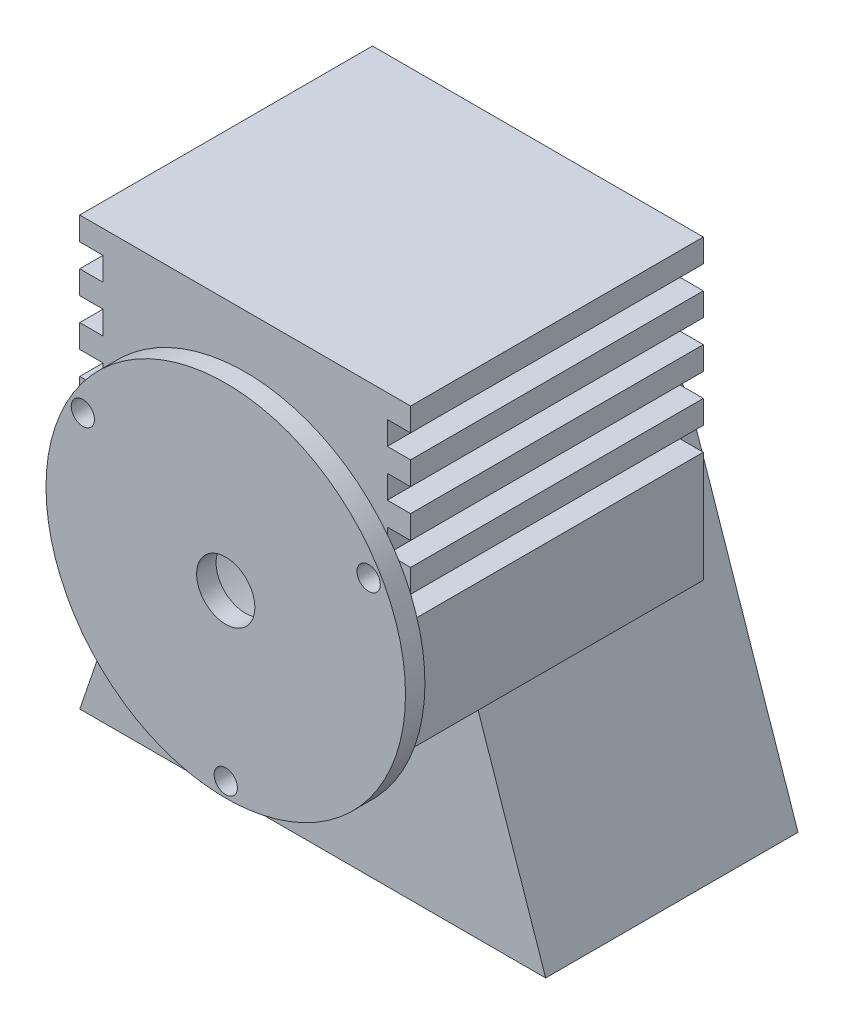
SolidWorks part; units mm, degrees
ref_plane "Front Plane" through (0, 0, 0) normal (0, 0, 1) x (1, 0, 0)
ref_plane "Top Plane" through (0, 0, 0) normal (0, 1, 0) x (1, 0, 0)
ref_plane "Right Plane" through (0, 0, 0) normal (1, 0, 0) x (0, 0, -1)
sketch "Sketch1" plane through (0, 0, 0) normal (0, 0, 1) x (1, 0, 0)
  line L0 (-150, -169) -> (150, -169)
  line L1 (-150, -169) -> (-82.8271, 28.212)
  line L3 (82.8271, 28.212) -> (150, -169)
  arc A0 (82.8271, 28.212) -> (-82.8271, 28.212) centre (0, 0) ccw
  point P5 (0, -169)
  dimension "D1" = 175
  dimension "D2" = 300
  dimension "D3" = 169
extrude "Boss-Extrude1" add sketch "Sketch1" along normal blind 162.5
sketch "Sketch2" plane through (0, 0, 162.5) normal (0, 0, 1) x (1, 0, 0)
  line L0 (-106.5324, 150) -> (106.5324, 150)
  line L1 (-106.5324, 150) -> (-106.5324, 135)
  line L2 (-106.5324, 135) -> (-91.5324, 135)
  line L3 (-91.5324, 135) -> (-91.5324, 120)
  line L4 (-91.5324, 120) -> (-106.5324, 120)
  line L5 (-106.5324, 120) -> (-106.5324, 105)
  line L6 (-106.5324, 105) -> (-91.5324, 105)
  line L7 (-91.5324, 105) -> (-91.5324, 90)
  line L8 (-91.5324, 90) -> (-106.5324, 90)
  line L9 (-106.5324, 90) -> (-106.5324, 75)
  line L10 (-106.5324, 75) -> (-91.5324, 75)
  line L11 (-91.5324, 75) -> (-91.5324, 60)
  line L12 (-91.5324, 60) -> (-106.5324, 60)
  line L13 (-106.5324, 60) -> (-106.5324, 45)
  line L14 (-106.5324, 45) -> (-91.5324, 45)
  line L15 (-91.5324, 45) -> (-91.5324, 30)
  line L16 (-91.5324, 30) -> (-106.5324, 30)
  line L17 (-106.5324, 30) -> (-106.5324, -41.3841)
  line L18 (-106.5324, -41.3841) -> (-82.8271, 28.212)
  line L19 (0, 0) -> (0, 150) construction
  line L20 (91.5324, 30) -> (106.5324, 30)
  line L21 (91.5324, 45) -> (91.5324, 30)
  line L22 (106.5324, 45) -> (91.5324, 45)
  line L23 (106.5324, 60) -> (106.5324, 45)
  line L24 (91.5324, 60) -> (106.5324, 60)
  line L25 (91.5324, 75) -> (91.5324, 60)
  line L26 (106.5324, 75) -> (91.5324, 75)
  line L27 (106.5324, 90) -> (106.5324, 75)
  line L28 (91.5324, 90) -> (106.5324, 90)
  line L29 (91.5324, 105) -> (91.5324, 90)
  line L30 (106.5324, 105) -> (91.5324, 105)
  line L31 (106.5324, 120) -> (106.5324, 105)
  line L32 (91.5324, 120) -> (106.5324, 120)
  line L33 (91.5324, 135) -> (91.5324, 120)
  line L34 (106.5324, 135) -> (91.5324, 135)
  line L35 (106.5324, 150) -> (106.5324, 135)
  line L36 (106.5324, 30) -> (106.5324, -41.3841)
  line L37 (106.5324, -41.3841) -> (82.8271, 28.212)
  arc A0 (82.8271, 28.212) -> (-82.8271, 28.212) centre (0, 0) ccw
  point P2 (0, 150)
  dimension "D1" = 150
  dimension "D2" = 15
  dimension "D3" = 15
  dimension "D4" = 15
extrude "Boss-Extrude2" add sketch "Sketch2" along normal blind 43.5 and the other way blind 145
sketch "Sketch3" plane through (0, 0, 162.5) normal (0, 0, 1) x (1, 0, 0)
  circle A0 centre (0, 0) radius 81.25
  dimension "D1" = 162.5
extrude "Cut-Extrude1" cut sketch "Sketch3" against normal blind 150
sketch "Sketch6" plane through (0, 0, 162.5) normal (0, 0, 1) x (1, 0, 0)
  circle A0 centre (0, 0) radius 87.5
  circle A1 centre (0, 0) radius 81.25
extrude "Boss-Extrude4" add sketch "Sketch6" along normal through all
sketch "Sketch7" plane through (0, 0, 206) normal (0, 0, 1) x (1, 0, 0)
  circle A0 centre (0, 0) radius 115.75
  dimension "D1" = 231.5
extrude "Boss-Extrude5" add sketch "Sketch7" along normal blind 12.5
sketch "Sketch8" plane through (0, 0, 218.5) normal (0, 0, 1) x (1, 0, 0)
  circle A1 centre (0, -106.25) radius 7.5
  circle A2 centre (-92.0152, 53.125) radius 7.5
  circle A3 centre (92.0152, 53.125) radius 7.5
  point P11 (0, 0)
  dimension "D2" = 15
  dimension "D3" = 3
extrude "Cut-Extrude2" cut sketch "Sketch8" against normal blind 12.5
sketch "Sketch9" plane through (0, 0, 218.5) normal (0, 0, 1) x (1, 0, 0)
  circle A0 centre (0, 0) radius 18.75
  dimension "D1" = 37.5
extrude "Cut-Extrude3" cut sketch "Sketch9" against normal through all both and the other way through all
